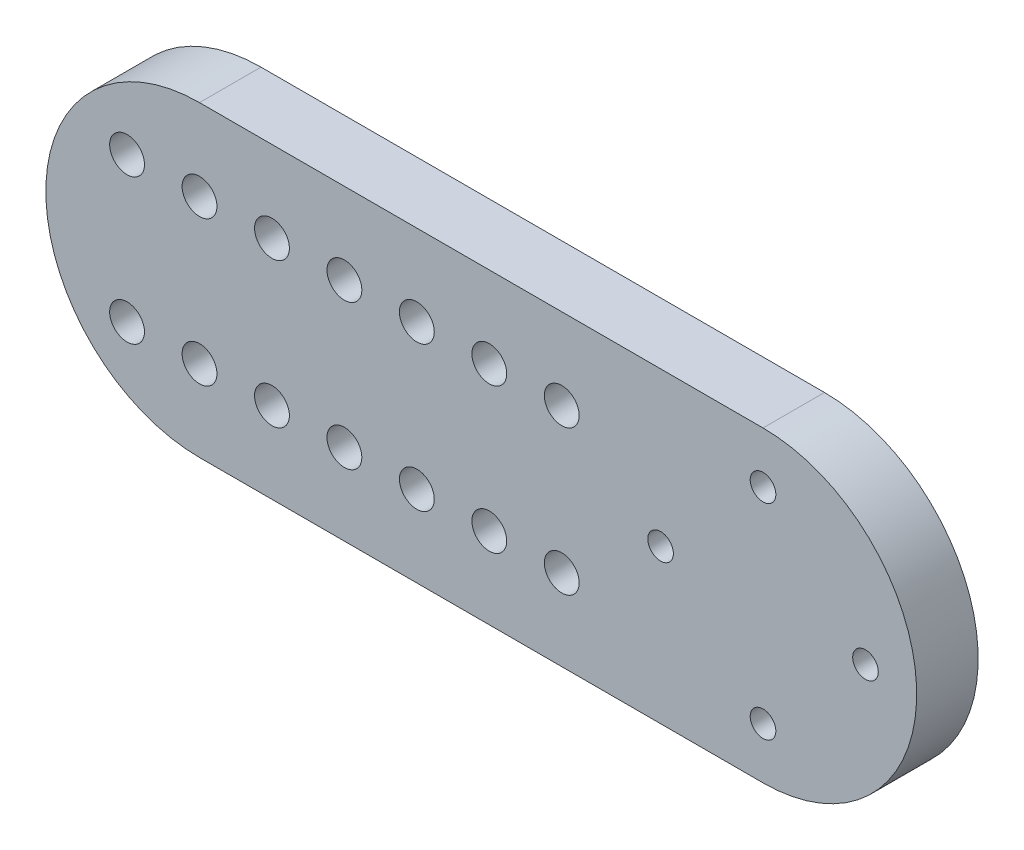
SolidWorks part; units mm, degrees
ref_plane "Спереди" through (0, 0, 0) normal (0, 0, 1) x (1, 0, 0)
ref_plane "Сверху" through (0, 0, 0) normal (0, 1, 0) x (1, 0, 0)
ref_plane "Справа" through (0, 0, 0) normal (1, 0, 0) x (0, 0, -1)
sketch "Эскиз1" plane through (0, 0, 0) normal (0, 0, 1) x (1, 0, 0)
  line L0 (-27.5, 0) -> (27.5, 0) construction
  line L1 (-27.5, 15) -> (27.5, 15)
  line L2 (-27.5, -15) -> (27.5, -15)
  arc A0 (-27.5, 15) -> (-27.5, -15) centre (-27.5, 0) ccw
  arc A1 (27.5, -15) -> (27.5, 15) centre (27.5, 0) ccw
  point P2 (0, 0)
  dimension "D1" = 15
  dimension "D2" = 55
extrude "Бобышка-Вытянуть1" add sketch "Эскиз1" along normal blind 6
sketch "Эскиз2" plane through (0, 0, 6) normal (0, 0, 1) x (1, 0, 0)
  line L0 (27.5, 10) -> (27.5, -10) construction
  line L1 (37.5, 0) -> (17.5, 0) construction
  line L2 (0, 0) -> (52.3387, 0) construction
  circle A0 centre (27.5, 0) radius 10 construction
  dimension "D1" = 20
  dimension "D2" = 0
  dimension "D3" = 90
  dimension "D4" = 14.1421
hole_wizard "Отверстие обработанное метчиком M3x0.51" positions "Эскиз4" profile "Эскиз3" tap size "M3x0.5" standard "Ansi Metric" end condition through all
sketch "Эскиз4" plane through (0, 0, 6) normal (0, 0, 1) x (1, 0, 0)
  point P0 (27.5, 10)
  point P3 (37.5, 0)
  point P6 (27.5, -10)
  point P9 (17.5, 0)
sketch "Эскиз3" plane through (27.5, 10, 6) normal (1, 0, 0) x (0, -1, 0)
  line L0 (0, 0) -> (0, 6)
  line L1 (0, 6) -> (1.25, 6)
  line L2 (1.25, 6) -> (1.25, 0)
  line L5 (1.25, 0) -> (0, 0)
  line L11 (0, -6.35) -> (0, 107.95) construction
  dimension "Диаметр проходного сверла" = 2.5
  dimension "Глубина проходного сверла" = 6
cosmetic thread "Отверстие резьбы1" parameters "D2"=3
cosmetic thread "Отверстие резьбы2" parameters "D2"=3
cosmetic thread "Отверстие резьбы3" parameters "D2"=3
cosmetic thread "Отверстие резьбы4" parameters "D2"=3
sketch "Эскиз5" plane through (0, 0, 6) normal (0, 0, 1) x (1, 0, 0)
  line L0 (-42.5, 0) -> (42.5, 0) construction
  line L1 (-34.5711, 7.0711) -> (-20.4289, -7.0711) construction
  line L2 (-20.4289, 7.0711) -> (-34.5711, -7.0711) construction
  line L3 (-20.4289, 7.0711) -> (-6.2868, -7.0711) construction
  line L4 (-6.2868, 7.0711) -> (-20.4289, -7.0711) construction
  line L5 (-6.2868, 7.0711) -> (7.8553, -7.0711) construction
  line L6 (7.8553, 7.0711) -> (-6.2868, -7.0711) construction
  line L7 (-46.9219, 7.0711) -> (16.9678, 7.0711) construction
  line L8 (-46.9219, -7.0711) -> (16.9678, -7.0711) construction
  circle A0 centre (-27.5, 0) radius 10 construction
  arc A1 (-27.5, 15) -> (-27.5, -15) centre (-27.5, 0) ccw construction
  arc A2 (27.5, -15) -> (27.5, 15) centre (27.5, 0) ccw construction
  circle A3 centre (-13.3579, 0) radius 10 construction
  circle A4 centre (0.7843, 0) radius 10 construction
  circle A5 centre (-20.4289, 0) radius 10 construction
  circle A6 centre (-6.2868, 0) radius 10 construction
  dimension "D1" = 20
  dimension "D3" = 20
  dimension "D4" = 20
  dimension "D5" = 20
  dimension "D6" = 20
  dimension "D2" = 45
hole_wizard "Отверстие с зазором M31" positions "Эскиз7" profile "Эскиз6" hole size "M3" standard "Ansi Metric" end condition through all
sketch "Эскиз7" plane through (0, 0, 6) normal (0, 0, 1) x (1, 0, 0)
  line L0 (-46.9219, -7.0711) -> (16.9678, -7.0711) construction
  line L1 (-46.9219, 7.0711) -> (16.9678, 7.0711) construction
  circle A0 centre (-20.4289, 0) radius 10 construction
  circle A1 centre (-6.2868, 0) radius 10 construction
  point P0 (-34.5711, 7.0711)
  point P3 (-20.4289, 7.0711)
  point P6 (-6.2868, 7.0711)
  point P9 (7.8553, 7.0711)
  point P12 (7.8553, -7.0711)
  point P15 (-6.2868, -7.0711)
  point P18 (-20.4289, -7.0711)
  point P21 (-34.5711, -7.0711)
  point P24 (-27.5, -7.0711)
  point P30 (-27.5, 7.0711)
  point P34 (-13.3579, 7.0711)
  point P38 (-13.3579, -7.0711)
  point P40 (0.7843, -7.0711)
  point P42 (0.7843, 7.0711)
sketch "Эскиз6" plane through (-34.5711, 7.0711, 6) normal (1, 0, 0) x (0, -1, 0)
  line L0 (0, 0) -> (0, 6)
  line L1 (0, 6) -> (1.7, 6)
  line L2 (1.7, 6) -> (1.7, 0)
  line L5 (1.7, 0) -> (0, 0)
  line L11 (0, -6.35) -> (0, 107.95) construction
  dimension "Диаметр сквозного отверстия" = 3.4
  dimension "Глубина сквозного отверстия" = 6
